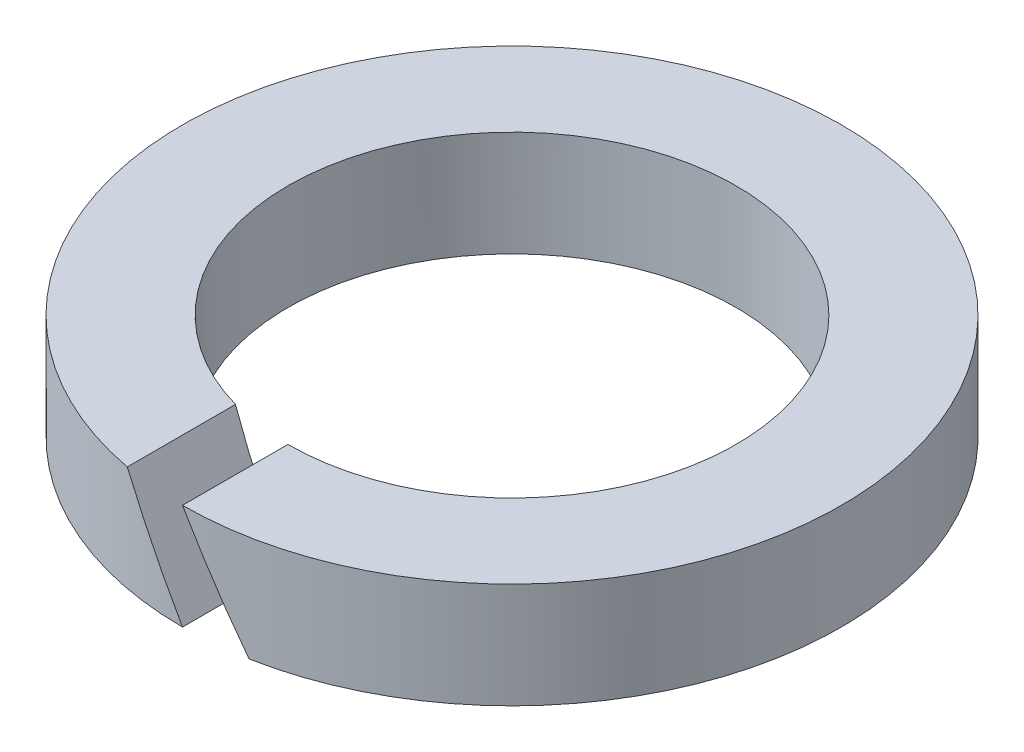
SolidWorks part; units mm, degrees
material "AISI 304"
ref_plane "前视基准面" through (0, 0, 0) normal (0, 0, 1) x (1, 0, 0)
ref_plane "上视基准面" through (0, 0, 0) normal (0, 1, 0) x (1, 0, 0)
ref_plane "右视基准面" through (0, 0, 0) normal (1, 0, 0) x (0, 0, -1)
other "Configuration Table"
sketch "草图1" plane through (0, 0, 0) normal (0, 0, 1) x (1, 0, 0)
  line L0 (0, 0) -> (0, 1983.4469) construction
  line L2 (1.7, 0) -> (2.5, 0)
  line L3 (1.7, 0) -> (1.7, 0.8)
  line L4 (1.7, 0.8) -> (2.5, 0.8)
  line L5 (2.5, 0) -> (2.5, 0.8)
  dimension "d" = 3.4
  dimension "b" = 0.8
  dimension "S" = 0.8
revolve "旋转1" add sketch "草图1" angle 360 about L0
sketch "草图2" plane through (0, 0, 0) normal (0, 0, 1) x (1, 0, 0)
  line L0 (0, 0) -> (0.4619, 0)
  line L1 (0.4619, 0) -> (0, 0.8)
  line L2 (2.5, 0.8) -> (-2.5, 0.8) construction
  line L3 (0, 0.8) -> (-0.4619, 0.8)
  line L4 (-0.4619, 0.8) -> (0, 0)
  dimension "m" = 0.4
extrude "切除-拉伸1" cut sketch "草图2" along normal through all
equation "\"b@草图1\"= \"S@草图1\""
